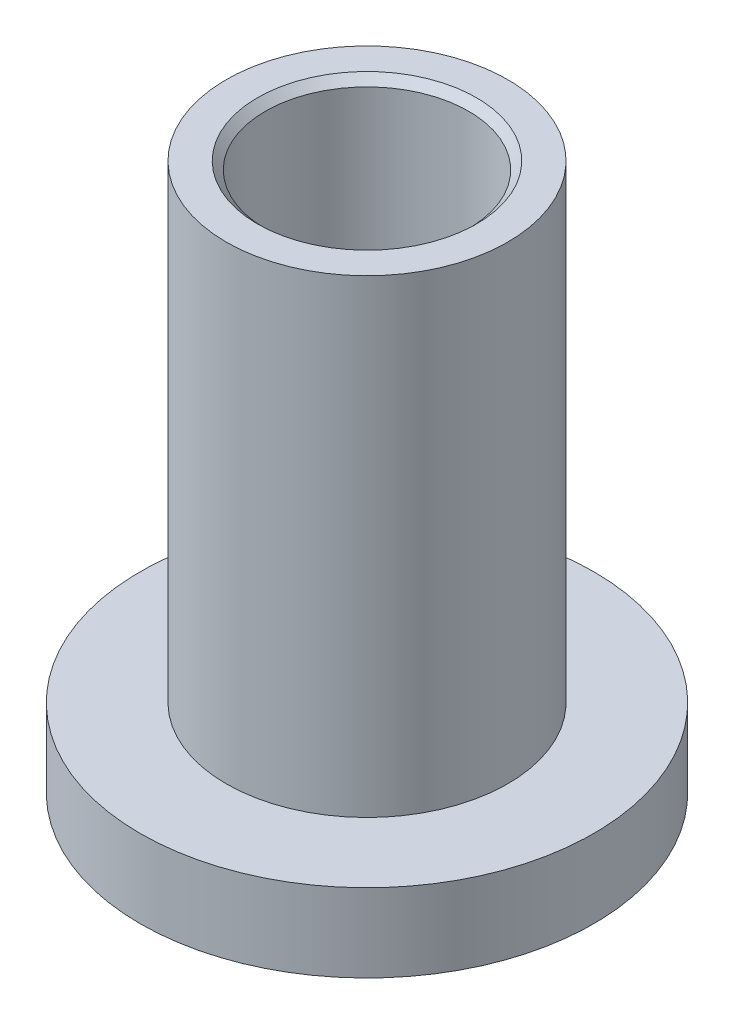
SolidWorks part; units mm, degrees
ref_plane "前视基准面" through (0, 0, 0) normal (0, 0, 1) x (1, 0, 0)
ref_plane "上视基准面" through (0, 0, 0) normal (0, 1, 0) x (1, 0, 0)
ref_plane "右视基准面" through (0, 0, 0) normal (1, 0, 0) x (0, 0, -1)
sketch "草图1" plane through (0, 0, 0) normal (0, 1, 0) x (1, 0, 0)
  circle A0 centre (0, 0) radius 29
  dimension "D1" = 58
extrude "凸台-拉伸1" add sketch "草图1" along normal blind 10 contours A0
sketch "草图2" plane through (0, 10, 0) normal (0, 1, 0) x (1, 0, 0)
  circle A0 centre (0, 0) radius 18
  circle A1 centre (0, 0) radius 13
  dimension "D1" = 36
  dimension "D2" = 26
extrude "凸台-拉伸2" add sketch "草图2" along normal blind 60
chamfer "倒角1" distance 1 angle 45 1 edges at (0, 70, 13)
